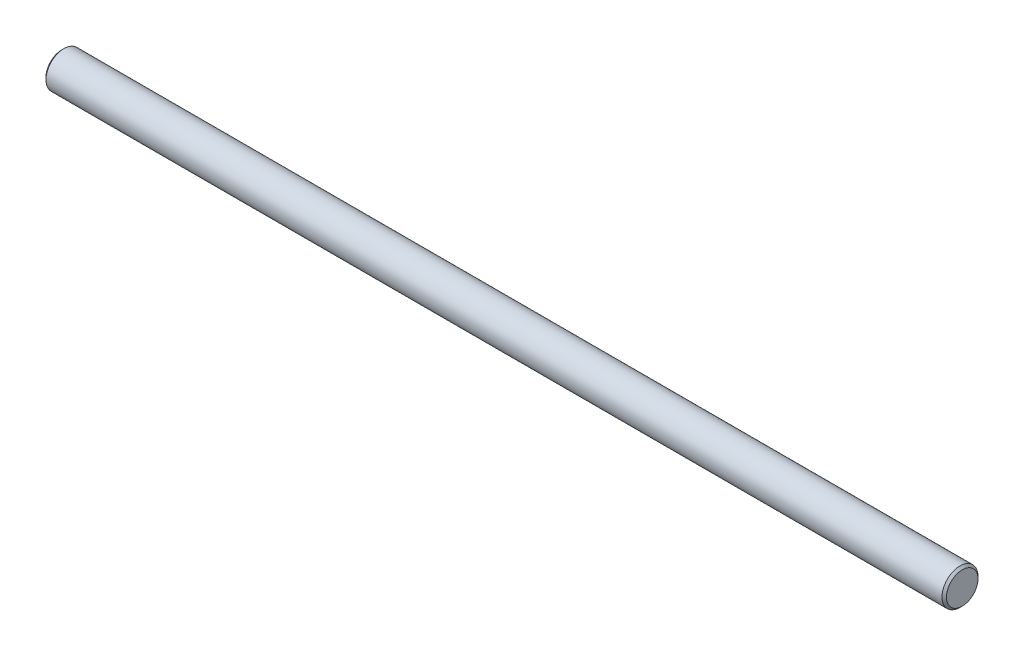
SolidWorks part; units mm, degrees
ref_plane "前视基准面" through (0, 0, 0) normal (0, 0, 1) x (1, 0, 0)
ref_plane "上视基准面" through (0, 0, 0) normal (0, 1, 0) x (1, 0, 0)
ref_plane "右视基准面" through (0, 0, 0) normal (1, 0, 0) x (0, 0, -1)
sketch "草图1" plane through (0, 0, 0) normal (1, 0, 0) x (0, 0, -1)
  circle A0 centre (0, 0) radius 4
  dimension "D1" = 8
extrude "凸台-拉伸1" add sketch "草图1" along normal blind 200
chamfer "倒角1" distance 0.5 angle 45 2 edges at (200, 0, -4) (0, 0, -4)
